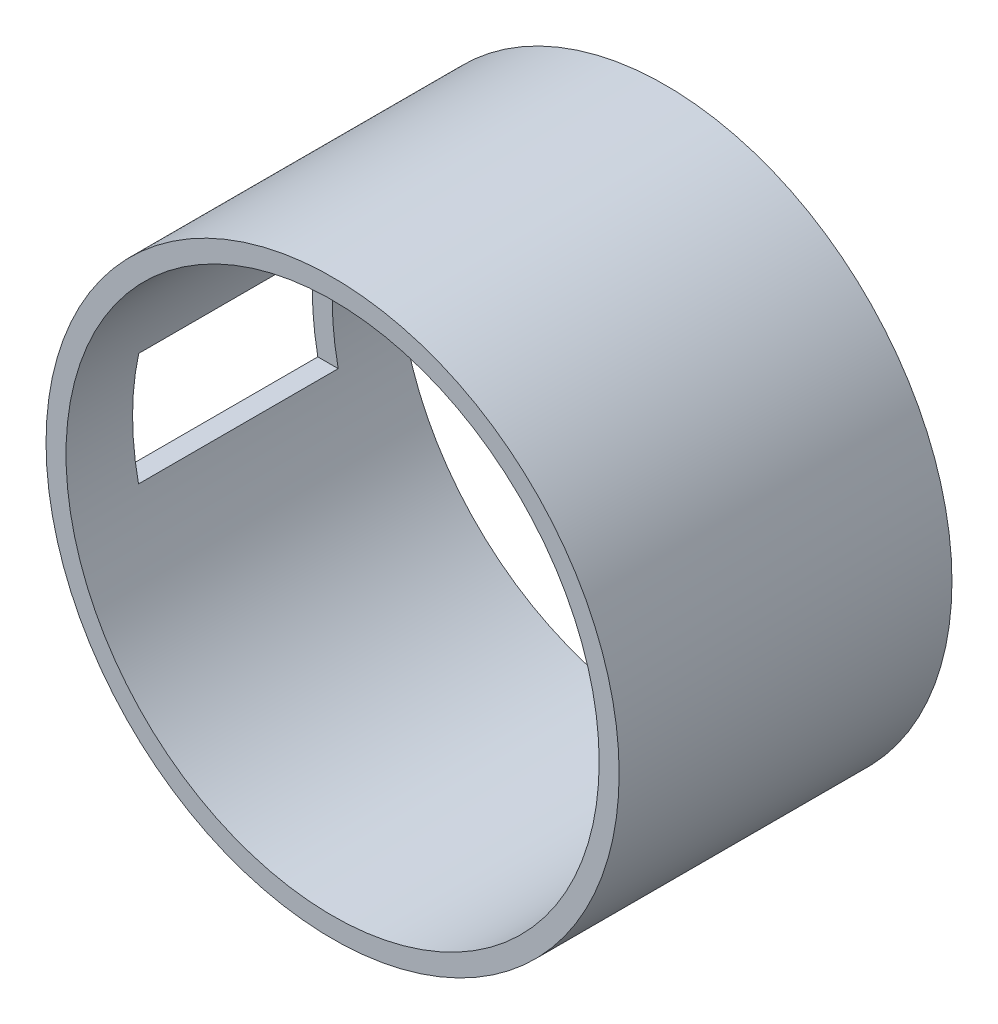
SolidWorks part; units mm, degrees
ref_plane "前视基准面" through (0, 0, 0) normal (0, 0, 1) x (1, 0, 0)
ref_plane "上视基准面" through (0, 0, 0) normal (0, 1, 0) x (1, 0, 0)
ref_plane "右视基准面" through (0, 0, 0) normal (1, 0, 0) x (0, 0, -1)
sketch "草图1" plane through (0, 0, 0) normal (0, 0, 1) x (1, 0, 0)
  circle A0 centre (0, 0) radius 8.01
  circle A1 centre (0, 0) radius 8.61
  dimension "D1" = 16.02
  dimension "D2" = 17.22
extrude "凸台-拉伸1" add sketch "草图1" along normal blind 10
sketch "草图2" plane through (0, 0, 10) normal (0, 0, 1) x (1, 0, 0)
  line L0 (-8.61, 0) -> (-8.01, 0) construction
  circle A0 centre (0, 0) radius 8.61 construction
  circle A1 centre (0, 0) radius 8.01 construction
ref_plane "基准面1" through (-8.61, 0, 0) normal (-1, 0, 0) x (0, 0, 1)
sketch "草图3" plane through (-8.61, 0, 0) normal (-1, 0, 0) x (0, 0, 1)
  line L0 (0, 0) -> (2, 0) construction
  line L1 (2, 0) -> (2, 1.7148) construction
  line L3 (2, 1.7148) -> (8, 1.7148)
  line L4 (2, 1.7148) -> (2, -1.6852)
  line L5 (2, -1.6852) -> (8, -1.6852)
  line L6 (8, 1.7148) -> (8, -1.6852)
  dimension "D1" = 6
  dimension "D2" = 3.4
extrude "切除-拉伸1" cut sketch "草图3" against normal blind 1.5
